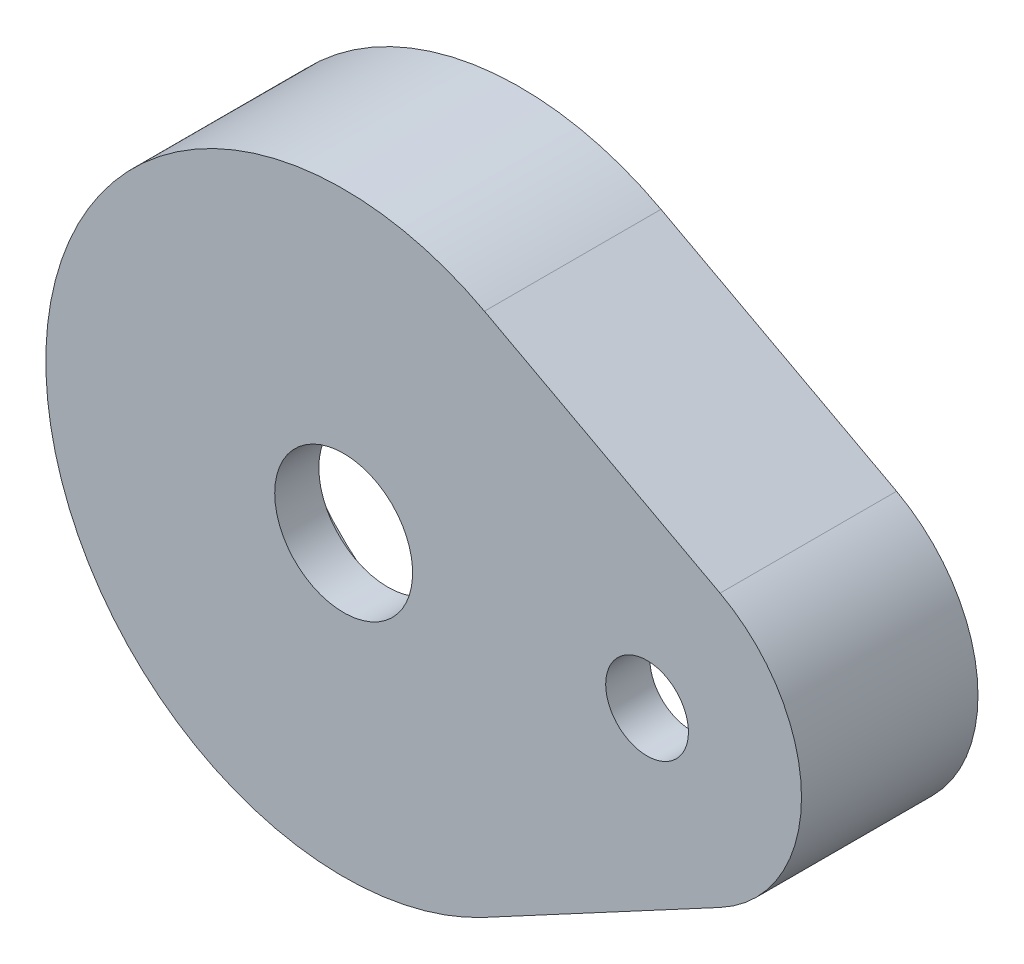
SolidWorks part; units mm, degrees
ref_plane "Front Plane" through (0, 0, 0) normal (0, 0, 1) x (1, 0, 0)
ref_plane "Top Plane" through (0, 0, 0) normal (0, 1, 0) x (1, 0, 0)
ref_plane "Right Plane" through (0, 0, 0) normal (1, 0, 0) x (0, 0, -1)
sketch "Sketch1" plane through (0, 0, 0) normal (0, 0, 1) x (1, 0, 0)
  line L0 (8.1049, 15.1083) -> (21.665, 7.8339)
  line L1 (8.1049, -15.1083) -> (21.665, -7.8339)
  arc A0 (8.1049, 15.1083) -> (8.1049, -15.1083) centre (0, 0) ccw
  arc A1 (21.665, -7.8339) -> (21.665, 7.8339) centre (17.4625, 0) ccw
  dimension "D1" = 34.29
  dimension "D2" = 17.78
  dimension "D3" = 17.4625
extrude "Boss-Extrude1" add sketch "Sketch1" along normal blind 10.16
sketch "Sketch2" plane through (0, 0, 0) normal (0, 0, 1) x (1, 0, 0)
  line L0 (6.9042, 12.8701) -> (20.4643, 5.5957)
  line L1 (6.9042, -12.8701) -> (20.4643, -5.5957)
  arc A0 (6.9042, 12.8701) -> (6.9042, -12.8701) centre (0, 0) ccw
  arc A1 (20.4643, -5.5957) -> (20.4643, 5.5957) centre (17.4625, 0) ccw
  dimension "D1" = 29.21
  dimension "D3" = 12.7
  dimension "D2" = 17.4625
extrude "Cut-Extrude1" cut sketch "Sketch2" along normal blind 7.62
sketch "Sketch3" plane through (0, 0, 7.62) normal (0, 0, -1) x (-1, 0, 0)
  circle A0 centre (0, 0) radius 3.9688
  circle A1 centre (-17.4625, 0) radius 2.3813
  dimension "D1" = 7.9375
  dimension "D3" = 4.7625
  dimension "D2" = 17.4625
extrude "Cut-Extrude2" cut sketch "Sketch3" against normal through all both and the other way through all
